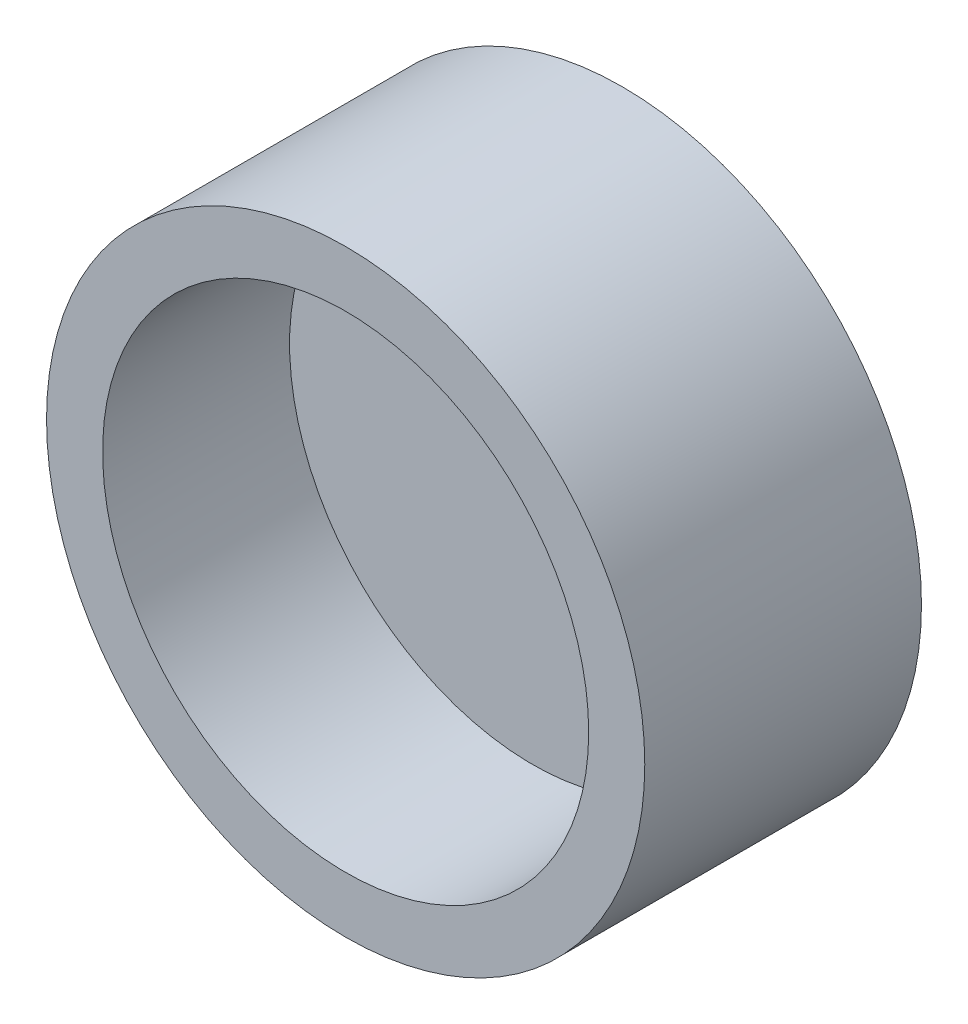
SolidWorks part; units mm, degrees
ref_plane "前视基准面" through (0, 0, 0) normal (0, 0, 1) x (1, 0, 0)
ref_plane "上视基准面" through (0, 0, 0) normal (0, 1, 0) x (1, 0, 0)
ref_plane "右视基准面" through (0, 0, 0) normal (1, 0, 0) x (0, 0, -1)
sketch "草图1" plane through (0, 0, 0) normal (0, 0, 1) x (1, 0, 0)
  circle A0 centre (0, 0) radius 8
  dimension "D1" = 16
extrude "凸台-拉伸1" add sketch "草图1" along normal blind 7.4
sketch "草图2" plane through (0, 0, 7.4) normal (0, 0, 1) x (1, 0, 0)
  circle A0 centre (0, 0) radius 6.5
  dimension "D1" = 13
extrude "切除-拉伸1" cut sketch "草图2" against normal blind 5
